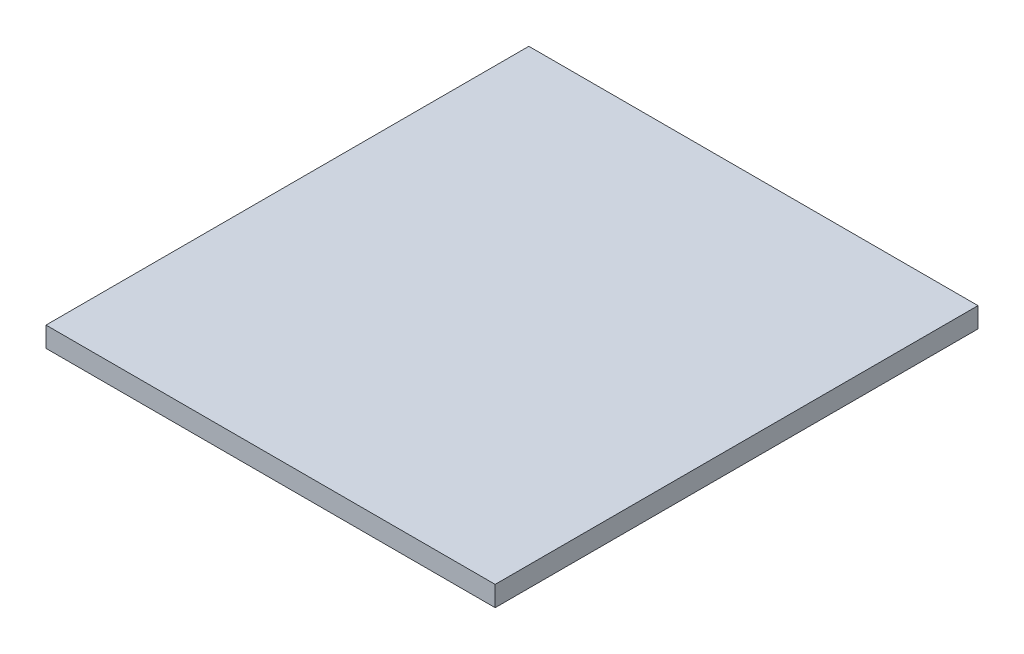
SolidWorks part; units mm, degrees
ref_plane "Alzado" through (0, 0, 0) normal (0, 0, 1) x (1, 0, 0)
ref_plane "Planta" through (0, 0, 0) normal (0, 1, 0) x (1, 0, 0)
ref_plane "Vista lateral" through (0, 0, 0) normal (1, 0, 0) x (0, 0, -1)
sketch "SkDobsonBaseInferior" plane through (0, 0, 0) normal (0, 1, 0) x (1, 0, 0)
  line L1 (-200, -215) -> (200, -215)
  line L2 (-200, -215) -> (-200, 215)
  line L3 (-200, 215) -> (200, 215)
  line L4 (200, -215) -> (200, 215)
extrude "DobsonBaseInferior" add sketch "SkDobsonBaseInferior" along normal blind 18 separate body
